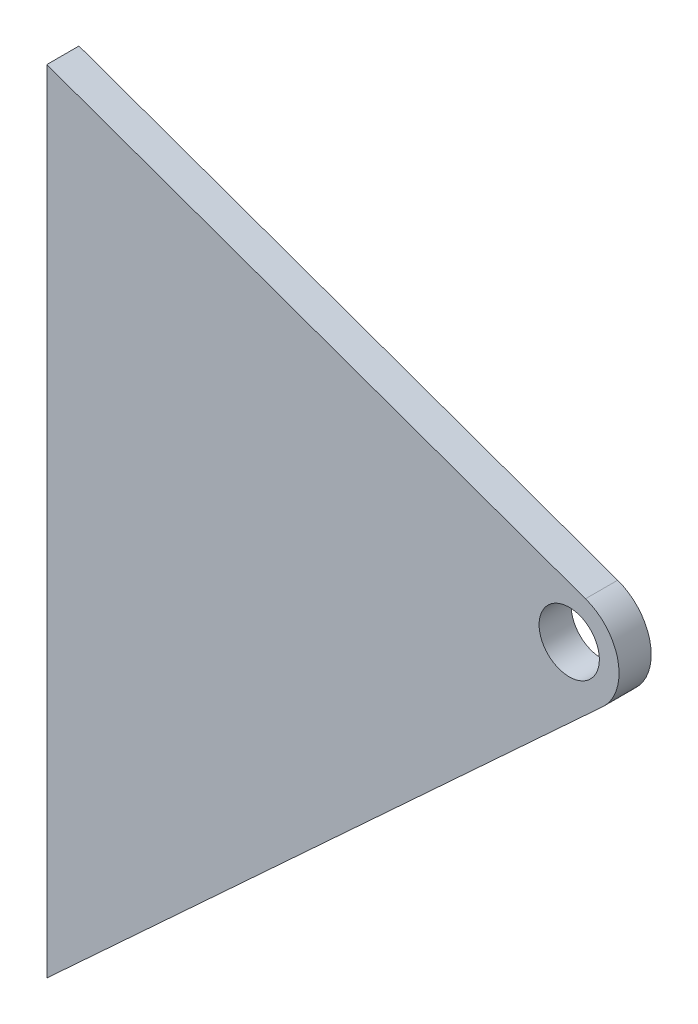
SolidWorks part; units mm, degrees
material "Zoltek Panex 33"
ref_plane "Front Plane" through (0, 0, 0) normal (0, 0, 1) x (1, 0, 0)
ref_plane "Top Plane" through (0, 0, 0) normal (0, 1, 0) x (1, 0, 0)
ref_plane "Right Plane" through (0, 0, 0) normal (1, 0, 0) x (0, 0, -1)
sketch "Sketch1" plane through (0, 0, 0) normal (0, 0, 1) x (1, 0, 0)
  line L0 (0, 0) -> (0, 250)
  line L1 (0, 0) -> (195.1, 180)
  line L2 (0, 250) -> (195.1, 180)
  circle A0 centre (165.1, 174.5) radius 9.525
  point P6 (0, 0)
  point P7 (140.9396, 121.1591)
  dimension "D4" = 19.05
  dimension "D1" = 250
  dimension "D2" = 180
  dimension "D3" = 165.1
  dimension "D5" = 30
  dimension "D6" = 5.5
extrude "Boss-Extrude1" add sketch "Sketch1" along normal blind 10.16
fillet "Fillet1" radius 16 1 edges at (195.1, 180, 5.08)
